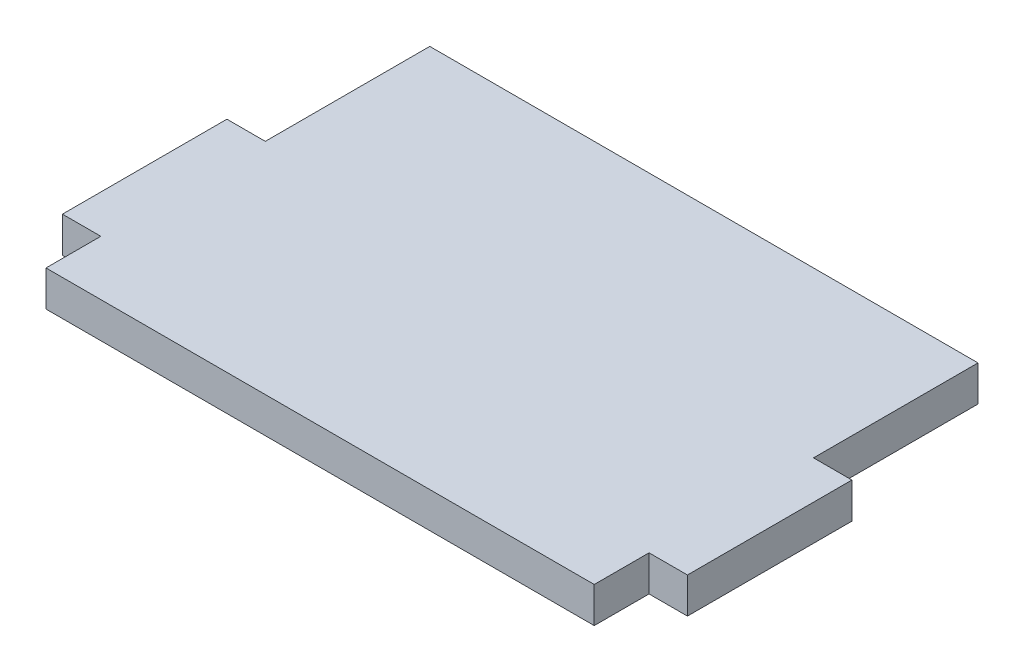
SolidWorks part; units mm, degrees
ref_plane "Front Plane" through (0, 0, 0) normal (0, 0, 1) x (1, 0, 0)
ref_plane "Top Plane" through (0, 0, 0) normal (0, 1, 0) x (1, 0, 0)
ref_plane "Right Plane" through (0, 0, 0) normal (1, 0, 0) x (0, 0, -1)
sketch "Sketch1" plane through (0, 0, 0) normal (0, 1, 0) x (1, 0, 0)
  line L1 (-10, 5) -> (10, 5)
  line L2 (-10, 5) -> (-10, -5)
  line L3 (-10, -5) -> (10, -5)
  line L4 (10, 5) -> (10, -5)
  line L5 (-10, 5) -> (10, -5) construction
  line L6 (-10, -5) -> (10, 5) construction
  point P0 (0, 0)
  dimension "D1" = 20
  dimension "D2" = 10
extrude "Boss-Extrude1" add sketch "Sketch1" along normal blind 1.3
sketch "Sketch2" plane through (0, 1.3, 0) normal (0, 1, 0) x (1, 0, 0)
  line L0 (-10, 5) -> (-10, -5) construction
  line L1 (-10, 3) -> (-11.4, 3)
  line L2 (-10, 3) -> (-10, -3)
  line L3 (-10, -3) -> (-11.4, -3)
  line L4 (-11.4, 3) -> (-11.4, -3)
  line L5 (10, -5) -> (10, 5) construction
  line L6 (10, 3) -> (11.4, 3)
  line L7 (10, 3) -> (10, -3)
  line L8 (10, -3) -> (11.4, -3)
  line L9 (11.4, 3) -> (11.4, -3)
  line L10 (-55, 0) -> (55, 0) construction
  dimension "D1" = 1.4
  dimension "D2" = 6
  dimension "D3" = 1.4
  dimension "D4" = 6
  dimension "D5" = 3
  dimension "D6" = 3
extrude "Boss-Extrude2" add sketch "Sketch2" against normal blind 1.3
sketch "Sketch3" plane through (0, 1.3, 0) normal (0, 1, 0) x (1, 0, 0)
  line L1 (-10, 5) -> (10, 5)
  line L2 (-10, 5) -> (-10, 9)
  line L3 (-10, 9) -> (10, 9)
  line L4 (10, 5) -> (10, 9)
  dimension "D1" = 4
extrude "Boss-Extrude3" add sketch "Sketch3" against normal blind 1.3
